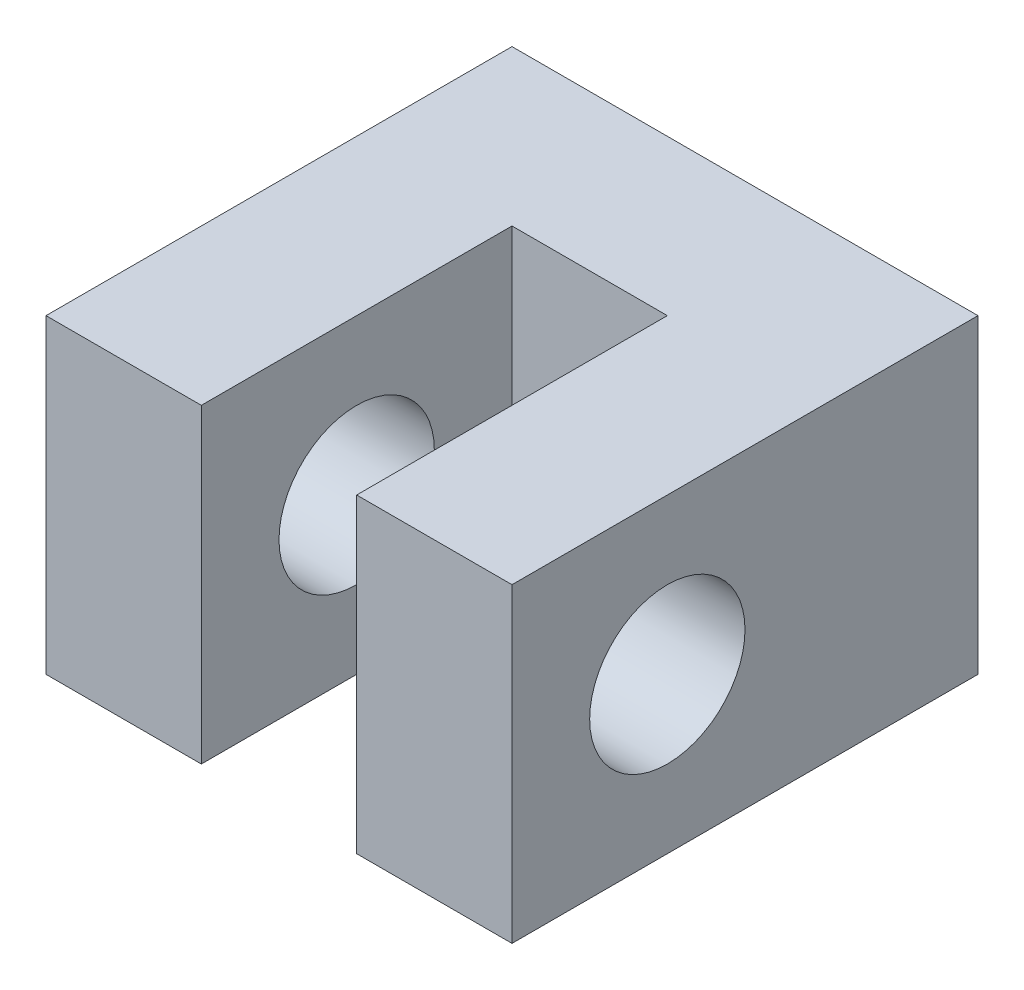
SolidWorks part; units mm, degrees
ref_plane "Front Plane" through (0, 0, 0) normal (0, 0, 1) x (1, 0, 0)
ref_plane "Top Plane" through (0, 0, 0) normal (0, 1, 0) x (1, 0, 0)
ref_plane "Right Plane" through (0, 0, 0) normal (1, 0, 0) x (0, 0, -1)
sketch "Sketch1" plane through (0, 0, 0) normal (0, 0, 1) x (1, 0, 0)
  circle A0 centre (0, 0) radius 3.175
  dimension "D1" = 6.35
sketch "Sketch2" plane through (0, 0, 0) normal (0, 1, 0) x (1, 0, 0)
  line L0 (-9.525, 0) -> (9.525, 0)
  line L1 (9.525, 0) -> (9.525, -19.05)
  line L2 (9.525, -19.05) -> (3.175, -19.05)
  line L3 (3.175, -19.05) -> (3.175, -6.35)
  line L4 (3.175, -6.35) -> (-3.175, -6.35)
  line L5 (-3.175, -6.35) -> (-3.175, -19.05)
  line L6 (-3.175, -19.05) -> (-9.525, -19.05)
  line L7 (-9.525, -19.05) -> (-9.525, 0)
  point P10 (0, 0)
  dimension "D1" = 6.35
  dimension "D2" = 6.35
  dimension "D3" = 6.35
  dimension "D4" = 6.35
  dimension "D5" = 19.05
  dimension "D6" = 19.05
extrude "Boss-Extrude2" add sketch "Sketch2" against normal mid plane 12.7
sketch "Sketch3" plane through (-9.525, 0, 0) normal (-1, 0, 0) x (0, 0, 1)
  line L0 (19.05, -6.35) -> (19.05, 6.35) construction
  circle A0 centre (12.7, 0) radius 3.175
  dimension "D2" = 6.35
  dimension "D1" = 6.35
extrude "Cut-Extrude1" cut sketch "Sketch3" against normal through all
extrude "Cut-Extrude2" cut sketch "Sketch1" along normal blind 2.54 contours A0
